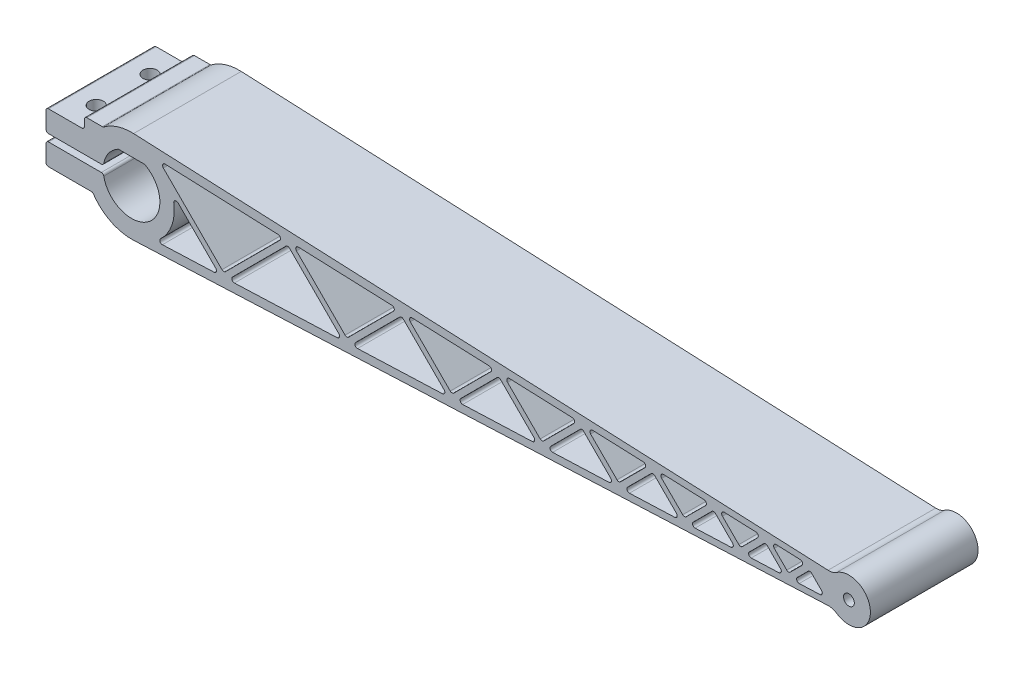
SolidWorks part; units mm, degrees
material "6061-T6 (SS)"
ref_plane "Front Plane" through (0, 0, 0) normal (0, 0, 1) x (1, 0, 0)
ref_plane "Top Plane" through (0, 0, 0) normal (0, 1, 0) x (1, 0, 0)
ref_plane "Right Plane" through (0, 0, 0) normal (1, 0, 0) x (0, 0, -1)
sketch "Sketch1" plane through (0, 0, 0) normal (0, 0, 1) x (1, 0, 0)
  line L0 (-4.9247, 0.5) -> (-11.9247, 0.5)
  line L1 (-4.9247, -0.5) -> (-11.9247, -0.5)
  line L2 (-11.9247, 0.5) -> (-11.9247, 3.5)
  line L3 (-11.9247, -0.5) -> (-11.9247, -3.5)
  line L4 (-11.9247, -3.5) -> (-5.4178, -3.5)
  line L5 (-11.9247, 3.5) -> (-5.4178, 3.5)
  line L6 (85.4894, -1.7821) -> (91.042, -1.5642)
  line L7 (88.3747, 1.1032) -> (91.042, -1.5642)
  line L8 (88.9635, 1.6457) -> (91.5863, -0.9771)
  line L9 (91.5863, -0.9771) -> (94.011, 1.4476)
  line L10 (0.287, 6.4436) -> (100.089, 1.998) construction
  line L11 (0.287, -6.4436) -> (100.089, -1.998) construction
  line L12 (-6.5712, 3.5) -> (-6.5712, 5.1)
  line L13 (-6.5712, 5.1) -> (-3.9487, 5.1)
  line L14 (100, 0) -> (99.145, -0.5186) construction
  line L15 (99.145, -0.5186) -> (97.8624, -1.2964) construction
  line L16 (3.2062, 5.0123) -> (97.8624, 1.2964) construction
  line L17 (97.8624, -1.2964) -> (3.2062, -5.0123) construction
  line L18 (3.2062, 5.0123) -> (12.8521, -4.6336) construction
  line L19 (12.8521, -4.6336) -> (12.8521, 4.6336) construction
  line L20 (12.8521, -4.6336) -> (21.7693, 4.2836) construction
  line L21 (21.7693, -4.2836) -> (21.7693, 4.2836) construction
  line L22 (21.7693, 4.2836) -> (30.0128, -3.96) construction
  line L23 (30.0128, 3.96) -> (30.0128, -3.96) construction
  line L24 (30.0128, -3.96) -> (37.6335, 3.6608) construction
  line L25 (37.6335, 3.6608) -> (44.6785, -3.3842) construction
  line L26 (44.6785, -3.3842) -> (51.1913, 3.1286) construction
  line L27 (51.1913, 3.1286) -> (57.2121, -2.8922) construction
  line L28 (57.2121, -2.8922) -> (62.778, 2.6737) construction
  line L29 (62.778, 2.6737) -> (67.9234, -2.4717) construction
  line L30 (67.9234, -2.4717) -> (72.6801, 2.285) construction
  line L31 (72.6801, 2.285) -> (77.0774, -2.1124) construction
  line L32 (77.0774, -2.1124) -> (81.1426, 1.9528) construction
  line L33 (81.1426, 1.9528) -> (84.9006, -1.8052) construction
  line L34 (84.9006, -1.8052) -> (88.3747, 1.6689) construction
  line L35 (88.3747, 1.6689) -> (91.5863, -1.5428) construction
  line L36 (91.5863, -1.5428) -> (94.5553, 1.4262) construction
  line L37 (94.5553, 1.4262) -> (97.3001, -1.3185) construction
  line L38 (97.3001, -1.3185) -> (99.8374, 1.2189) construction
  line L39 (37.6335, -3.6608) -> (37.6335, 3.6608) construction
  line L40 (44.6785, 3.3842) -> (44.6785, -3.3842) construction
  line L41 (51.1913, -3.1286) -> (51.1913, 3.1286) construction
  line L42 (57.2121, 2.8922) -> (57.2121, -2.8922) construction
  line L43 (62.778, -2.6737) -> (62.778, 2.6737) construction
  line L44 (67.9234, 2.4717) -> (67.9234, -2.4717) construction
  line L45 (72.6801, -2.285) -> (72.6801, 2.285) construction
  line L46 (77.0774, 2.1124) -> (77.0774, -2.1124) construction
  line L47 (81.1426, -1.9528) -> (81.1426, 1.9528) construction
  line L48 (84.9006, 1.8052) -> (84.9006, -1.8052) construction
  line L49 (88.3747, -1.6689) -> (88.3747, 1.6689) construction
  line L50 (91.5863, 1.5428) -> (91.5863, -1.5428) construction
  line L51 (94.5553, 1.4262) -> (94.5553, -1.4262) construction
  line L52 (97.3001, -1.3185) -> (97.3001, 1.3185) construction
  line L53 (99.8374, 1.2189) -> (99.8374, -1.2189) construction
  line L54 (2.9233, 4.7294) -> (12.5692, -4.9165) construction
  line L55 (13.2521, -4.6336) -> (13.2521, 4.6336) construction
  line L56 (13.1349, -4.9165) -> (22.0521, 4.0007) construction
  line L57 (22.1693, -4.2836) -> (22.1693, 4.2836) construction
  line L58 (21.4864, 4.0007) -> (29.7299, -4.2428) construction
  line L59 (29.6128, 3.96) -> (29.6128, -3.96) construction
  line L60 (30.2956, -4.2428) -> (37.9164, 3.3779) construction
  line L61 (37.3507, 3.3779) -> (44.3957, -3.6671) construction
  line L62 (44.9614, -3.6671) -> (51.4742, 2.8457) construction
  line L63 (50.9085, 2.8457) -> (56.9292, -3.175) construction
  line L64 (57.4949, -3.175) -> (63.0608, 2.3909) construction
  line L65 (62.4951, 2.3909) -> (67.6406, -2.7546) construction
  line L66 (68.2062, -2.7546) -> (72.9629, 2.0021) construction
  line L67 (72.3972, 2.0021) -> (76.7946, -2.3952) construction
  line L68 (77.3603, -2.3952) -> (81.4254, 1.6699) construction
  line L69 (80.8597, 1.6699) -> (84.6177, -2.0881) construction
  line L70 (85.1834, -2.0881) -> (88.6575, 1.386) construction
  line L71 (88.0918, 1.386) -> (91.3035, -1.8256) construction
  line L72 (91.8692, -1.8256) -> (94.8382, 1.1434) construction
  line L73 (94.2725, 1.1434) -> (97.0172, -1.6013) construction
  line L74 (97.5829, -1.6013) -> (99.4374, 0.2532) construction
  line L75 (99.4374, 0.2532) -> (99.4374, -1.2189) construction
  line L76 (38.0335, -3.6608) -> (38.0335, 3.6608) construction
  line L77 (44.2785, 3.3842) -> (44.2785, -3.3842) construction
  line L78 (51.5913, -3.1286) -> (51.5913, 3.1286) construction
  line L79 (56.8121, 2.8922) -> (56.8121, -2.8922) construction
  line L80 (63.178, -2.6737) -> (63.178, 2.6737) construction
  line L81 (67.5234, 2.4717) -> (67.5234, -2.4717) construction
  line L82 (73.0801, -2.285) -> (73.0801, 2.285) construction
  line L83 (76.6774, 2.1124) -> (76.6774, -2.1124) construction
  line L84 (81.5426, -1.9528) -> (81.5426, 1.9528) construction
  line L85 (84.5006, 1.8052) -> (84.5006, -1.8052) construction
  line L86 (88.7747, -1.6689) -> (88.7747, 1.6689) construction
  line L87 (91.1863, 1.5428) -> (91.1863, -1.5428) construction
  line L88 (94.1553, 1.4262) -> (94.1553, -1.4262) construction
  line L89 (97.7001, -1.3185) -> (97.7001, 1.3185) construction
  line L90 (3.489, 5.2951) -> (13.1349, -4.3508) construction
  line L91 (12.4521, -4.6336) -> (12.4521, 4.6336) construction
  line L92 (12.5692, -4.3508) -> (21.4864, 4.5664) construction
  line L93 (21.3693, -4.2836) -> (21.3693, 4.2836) construction
  line L94 (22.0521, 4.5664) -> (30.2956, -3.6771) construction
  line L95 (30.4128, 3.96) -> (30.4128, -3.96) construction
  line L96 (29.7299, -3.6771) -> (37.3507, 3.9436) construction
  line L97 (37.9164, 3.9436) -> (44.9614, -3.1014) construction
  line L98 (44.3957, -3.1014) -> (50.9085, 3.4114) construction
  line L99 (51.4742, 3.4114) -> (57.4949, -2.6094) construction
  line L100 (56.9292, -2.6094) -> (62.4951, 2.9565) construction
  line L101 (63.0608, 2.9565) -> (68.2062, -2.1889) construction
  line L102 (67.6406, -2.1889) -> (72.3972, 2.5678) construction
  line L103 (72.9629, 2.5678) -> (77.3603, -1.8295) construction
  line L104 (76.7946, -1.8295) -> (80.8597, 2.2356) construction
  line L105 (81.4254, 2.2356) -> (85.1834, -1.5224) construction
  line L106 (84.6177, -1.5224) -> (88.0918, 1.9517) construction
  line L107 (88.6575, 1.9517) -> (91.8692, -1.2599) construction
  line L108 (91.3035, -1.2599) -> (94.2725, 1.7091) construction
  line L109 (94.8382, 1.7091) -> (97.5829, -1.0356) construction
  line L110 (97.0172, -1.0356) -> (100.2374, 2.1846) construction
  line L111 (100.2374, 2.1846) -> (100.2374, -1.2189) construction
  line L112 (37.2335, -3.6608) -> (37.2335, 3.6608) construction
  line L113 (45.0785, 3.3842) -> (45.0785, -3.3842) construction
  line L114 (50.7913, -3.1286) -> (50.7913, 3.1286) construction
  line L115 (57.6121, 2.8922) -> (57.6121, -2.8922) construction
  line L116 (62.378, -2.6737) -> (62.378, 2.6737) construction
  line L117 (68.3234, 2.4717) -> (68.3234, -2.4717) construction
  line L118 (72.2801, -2.285) -> (72.2801, 2.285) construction
  line L119 (77.4774, 2.1124) -> (77.4774, -2.1124) construction
  line L120 (80.7426, -1.9528) -> (80.7426, 1.9528) construction
  line L121 (85.3006, 1.8052) -> (85.3006, -1.8052) construction
  line L122 (87.9747, -1.6689) -> (87.9747, 1.6689) construction
  line L123 (91.9863, 1.5428) -> (91.9863, -1.5428) construction
  line L124 (94.9553, 1.4262) -> (94.9553, -1.4262) construction
  line L125 (96.9001, -1.3185) -> (96.9001, 1.3185) construction
  line L126 (5.5757, 2.0771) -> (12.3078, -4.655)
  line L127 (12.3078, -4.655) -> (3.2062, -5.0123)
  line L128 (12.8521, -4.0679) -> (3.795, 4.9892)
  line L129 (3.795, 4.9892) -> (21.2249, 4.3049)
  line L130 (13.4409, -4.6105) -> (29.4685, -3.9813)
  line L131 (29.4685, -3.9813) -> (21.7693, 3.7179)
  line L132 (21.2249, 4.3049) -> (12.8521, -4.0679)
  line L133 (21.7693, 3.7179) -> (13.4409, -4.6105)
  line L134 (22.3581, 4.2605) -> (37.0892, 3.6822)
  line L135 (37.0892, 3.6822) -> (30.0128, -3.3943)
  line L136 (30.0128, -3.3943) -> (22.3581, 4.2605)
  line L137 (30.6016, -3.9368) -> (44.1342, -3.4056)
  line L138 (44.1342, -3.4056) -> (37.6335, 3.0951)
  line L139 (37.6335, 3.0951) -> (30.6016, -3.9368)
  line L140 (38.2223, 3.6377) -> (44.6785, -2.8185)
  line L141 (44.6785, -2.8185) -> (50.647, 3.1499)
  line L142 (50.647, 3.1499) -> (38.2223, 3.6377)
  line L143 (45.2673, -3.3611) -> (56.6678, -2.9136)
  line L144 (56.6678, -2.9136) -> (51.1913, 2.5629)
  line L145 (51.1913, 2.5629) -> (45.2673, -3.3611)
  line L146 (51.7801, 3.1054) -> (57.2121, -2.3265)
  line L147 (57.2121, -2.3265) -> (62.2337, 2.6951)
  line L148 (62.2337, 2.6951) -> (51.7801, 3.1054)
  line L149 (57.8009, -2.8691) -> (67.3791, -2.4931)
  line L150 (67.3791, -2.4931) -> (62.778, 2.108)
  line L151 (62.778, 2.108) -> (57.8009, -2.8691)
  line L152 (63.3668, 2.6506) -> (67.9234, -1.906)
  line L153 (67.9234, -1.906) -> (72.1358, 2.3063)
  line L154 (72.1358, 2.3063) -> (63.3668, 2.6506)
  line L155 (68.5122, -2.4486) -> (72.6801, 1.7193)
  line L156 (72.6801, 1.7193) -> (76.5331, -2.1337)
  line L157 (76.5331, -2.1337) -> (68.5122, -2.4486)
  line L158 (73.2689, 2.2619) -> (77.0774, -1.5467)
  line L159 (80.5982, 1.9741) -> (77.0774, -1.5467)
  line L160 (80.5982, 1.9741) -> (73.2689, 2.2619)
  line L161 (77.6662, -2.0892) -> (81.1426, 1.3871)
  line L162 (81.1426, 1.3871) -> (84.3563, -1.8266)
  line L163 (84.3563, -1.8266) -> (77.6662, -2.0892)
  line L164 (94.011, 1.4476) -> (88.9635, 1.6457)
  line L165 (81.7314, 1.9297) -> (87.8304, 1.6902)
  line L166 (87.8304, 1.6902) -> (84.9006, -1.2396)
  line L167 (84.9006, -1.2396) -> (81.7314, 1.9297)
  line L168 (85.4894, -1.7821) -> (88.3747, 1.1032)
  line L169 (92.1751, -1.5197) -> (96.7557, -1.3399)
  line L170 (96.7557, -1.3399) -> (94.5553, 0.8605)
  line L171 (94.5553, 0.8605) -> (92.1751, -1.5197)
  line L172 (-8.6712, 3.5) -> (-8.6712, -3.5) construction
  line L173 (-1.831, 3.5) -> (1.831, 3.5)
  line L174 (-4.9247, 0.5) -> (-3.9182, 0.5)
  line L175 (97.092, -2.1315) -> (0.287, -6.4436)
  line L176 (0.287, 6.4436) -> (97.092, 2.1315)
  line L177 (-4.9247, -0.5) -> (-3.9182, -0.5)
  line L218 (99.8374, 1.2189) -> (102.1831, -1.1268) construction
  line L219 (102.1831, -1.1268) -> (104.3515, 1.0417) construction
  line L220 (104.3515, 1.0417) -> (106.3562, -0.963) construction
  line L224 (99.5546, 0.936) -> (102.1831, -1.6925) construction
  line L225 (102.1831, -1.6925) -> (104.3515, 0.476) construction
  line L226 (104.3515, 0.476) -> (106.0733, -1.2458) construction
  line L227 (100.1203, 1.5017) -> (102.1831, -0.5611) construction
  line L228 (102.1831, -0.5611) -> (104.3515, 1.6074) construction
  line L229 (104.3515, 1.6074) -> (106.639, -0.6801) construction
  circle A0 centre (0, 0) radius 3.95
  arc A1 (3.2062, 5.0123) -> (3.2062, -5.0123) centre (0, 0) cw construction
  arc A2 (0.287, 6.4436) -> (-5.4178, 3.5) centre (0, 0) ccw
  arc A3 (0.287, -6.4436) -> (-5.4178, -3.5) centre (0, 0) cw
  arc A4 (100.089, 1.998) -> (100.089, -1.998) centre (100, 0) cw construction
  circle A5 centre (100, 0) radius 1
  arc A6 (5.5757, 2.0771) -> (3.2062, -5.0123) centre (0, 0) cw
  arc A7 (-4.9247, -0.5) -> (-4.9247, 0.5) centre (0, 0) ccw construction
  arc A10 (98.3086, 2.4777) -> (98.3086, -2.4777) centre (100, 0) cw
  arc A11 (98.3086, 2.4777) -> (97.092, 2.1315) centre (97.181, 4.1295) cw
  arc A12 (98.3086, -2.4777) -> (97.092, -2.1315) centre (97.181, -4.1295) ccw
  point P1 (3.2062, 5.0123)
  point P5 (3.2062, -5.0123)
  point P30 (97.8624, 1.2964)
  point P31 (97.8624, -1.2964)
  point P265 (97.8551, 2.0975)
  point P268 (97.8551, -2.0975)
  dimension "D4" = 4.95
  dimension "D9" = 3
  dimension "D10" = 2
  dimension "D11" = 1
  dimension "D13" = 2
  dimension "D6" = 1.5
  dimension "D12" = 1
  dimension "D27" = 7.9
  dimension "D3" = 3
  dimension "D5" = 1.5
  dimension "D7" = 1
  dimension "D8" = 7
  dimension "D14" = 100
  dimension "D15" = 1.6
  dimension "D16" = 1.3
  dimension "D17" = 1.3
  dimension "D18" = 0.8
  dimension "D19" = 2.1
  dimension "D20" = 0.8
  dimension "D21" = 45
  dimension "D22" = 135
  dimension "D23" = 0.4
  dimension "D28" = 3.5
  dimension "D24" = 0.4
  dimension "D25" = 0.4
  dimension "D26" = 0.4
extrude "Boss-Extrude1" add sketch "Sketch1" against normal blind 15
cosmetic thread "Cosmetic Thread1" parameters "D1"=15, "D2"=2
sketch "Sketch2" plane through (0, 3.5, 0) normal (0, 1, 0) x (1, 0, 0)
  line L0 (-6.5712, 15) -> (-6.5712, 0) construction
  line L1 (-8.6712, 7.5) -> (-11.9247, 7.5) construction
  line L2 (-8.6712, 11.25) -> (-8.6712, 7.5) construction
  line L3 (-8.6712, 7.5) -> (-8.6712, 3.75) construction
  line L4 (-11.9247, 15) -> (-11.9247, 0) construction
  circle A0 centre (-8.6712, 11.25) radius 1
  circle A1 centre (-8.6712, 3.75) radius 1
  dimension "D1" = 2
  dimension "D2" = 3.75
  dimension "D3" = 2.1
extrude "Cut-Extrude1" cut sketch "Sketch2" against normal through all
fillet "Fillet1" radius 0.35 63 edges at (3.2062, -5.0123, -7.5) (12.3078, -4.655, -7.5) (5.5757, 2.0771, -7.5) (3.795, 4.9892, -7.5) (-11.9247, -3.5, -7.5) (-11.9247, -0.5, -7.5) (-11.9247, 0.5, -7.5) (-11.9247, 3.5, -7.5) (-5.4178, -3.5, -7.5) (29.4685, -3.9813, -7.5) (44.1342, -3.4056, -7.5) (56.6678, -2.9136, -7.5) (67.3791, -2.4931, -7.5) (76.5331, -2.1337, -7.5) (84.3563, -1.8266, -7.5) (77.6662, -2.0892, -7.5) (68.5122, -2.4486, -7.5) (57.8009, -2.8691, -7.5) (45.2673, -3.3611, -7.5) (30.6016, -3.9368, -7.5) (13.4409, -4.6105, -7.5) (12.8521, -4.0679, -7.5) (30.0128, -3.3943, -7.5) (44.6785, -2.8185, -7.5) (57.2121, -2.3265, -7.5) (67.9234, -1.906, -7.5) (77.0774, -1.5467, -7.5) (84.9006, -1.2396, -7.5) (81.1426, 1.3871, -7.5) (72.6801, 1.7193, -7.5) (62.778, 2.108, -7.5) (51.1913, 2.5629, -7.5) (21.7693, 3.7179, -7.5) (37.6335, 3.0951, -7.5) (21.2249, 4.3049, -7.5) (37.0892, 3.6822, -7.5) (50.647, 3.1499, -7.5) (62.2337, 2.6951, -7.5) (72.1358, 2.3063, -7.5) (80.5982, 1.9741, -7.5) (87.8304, 1.6902, -7.5) (81.7314, 1.9297, -7.5) (73.2689, 2.2619, -7.5) (63.3668, 2.6506, -7.5) (51.7801, 3.1054, -7.5) (38.2223, 3.6377, -7.5) (22.3581, 4.2605, -7.5) (88.3747, 1.1032, -7.5) (91.042, -1.5642, -7.5) (85.4894, -1.7821, -7.5) (92.1751, -1.5197, -7.5) (96.7557, -1.3399, -7.5) (94.011, 1.4476, -7.5) (94.5553, 0.8605, -7.5) (88.9635, 1.6457, -7.5) (91.5863, -0.9771, -7.5) (-3.9487, 5.1, -7.5) (-6.5712, 5.1, -7.5) (-6.5712, 3.5, -7.5) (-3.9182, -0.5, -7.5) (-3.9182, 0.5, -7.5) (-1.831, 3.5, -7.5) (1.831, 3.5, -7.5)
sketch "Sketch3" plane through (0, 0, -15) normal (0, 0, -1) x (-1, 0, 0)
  point P0 (0, 0)
sketch "Sketch4" plane through (0, 0, 0) normal (0, 0, 1) x (1, 0, 0)
  circle A0 centre (100, 0) radius 0.75
  circle A1 centre (100, 0) radius 1
  circle A2 centre (100, 0) radius 1
  dimension "D2" = 1.5
  dimension "D1" = 0
extrude "Boss-Extrude2" add sketch "Sketch4" against normal up to surface (15 mm away) up to face at (8.1068, 0.9865, -15)
